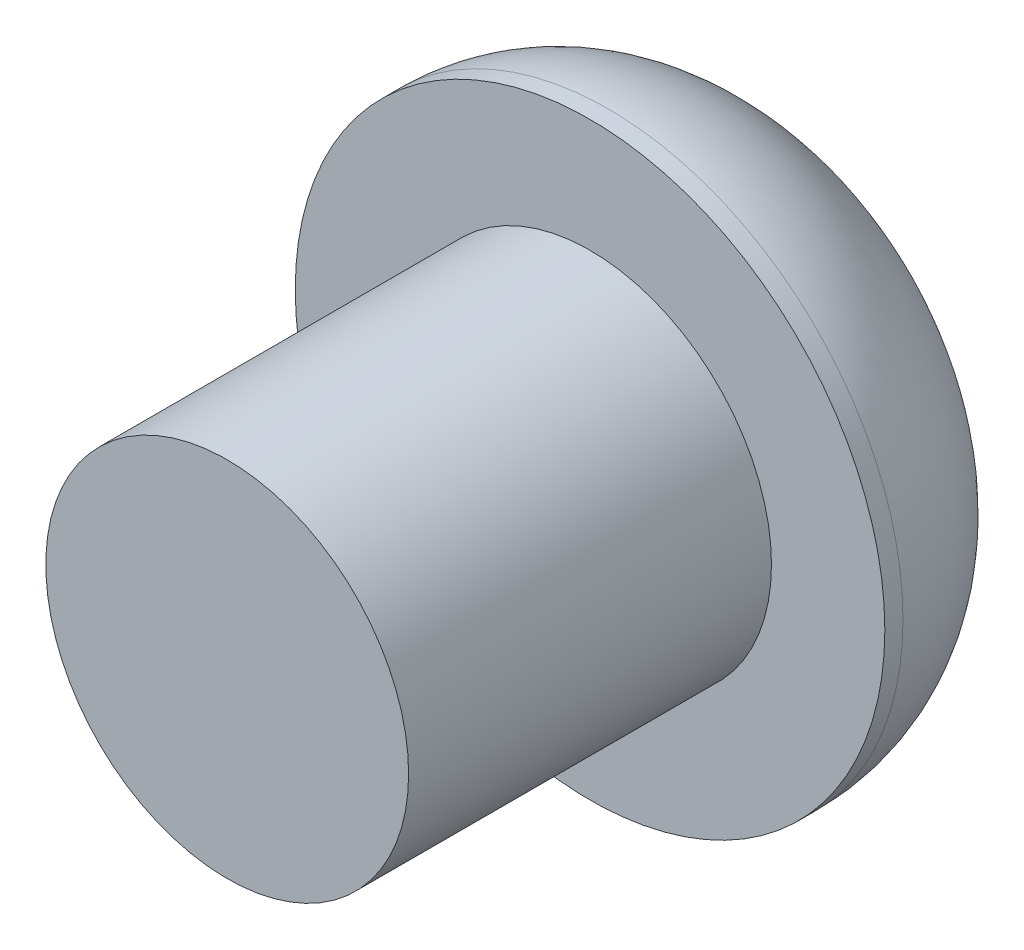
SolidWorks part; units mm, degrees
ref_plane "前视基准面" through (0, 0, 0) normal (0, 0, 1) x (1, 0, 0)
ref_plane "上视基准面" through (0, 0, 0) normal (0, 1, 0) x (1, 0, 0)
ref_plane "右视基准面" through (0, 0, 0) normal (1, 0, 0) x (0, 0, -1)
sketch "草图1" plane through (0, 0, 0) normal (0, 0, 1) x (1, 0, 0)
  circle A0 centre (0, 0) radius 2
  dimension "D1" = 4
extrude "凸台-拉伸1" add sketch "草图1" along normal blind 4
sketch "草图2" plane through (0, 0, 0) normal (0, 0, -1) x (-1, 0, 0)
  circle A0 centre (0, 0) radius 3.25
  dimension "D1" = 6.5
extrude "凸台-拉伸2" add sketch "草图2" along normal blind 2.2
fillet "圆角1" radius 2 1 edges at (-3.25, 0, -2.2)
sketch "草图3" plane through (0, 0, -2.2) normal (0, 0, -1) x (-1, 0, 0)
  line L0 (0, 3.24) -> (0, -3.24) construction
  line L1 (-3.24, 0) -> (3.24, 0) construction
  line L2 (-3.24, 0.25) -> (3.24, 0.25) construction
  line L3 (0.25, 3.24) -> (0.25, -3.24) construction
  line L4 (-3.24, -0.25) -> (3.24, -0.25) construction
  line L5 (-0.25, 3.24) -> (-0.25, -3.24) construction
  line L7 (3.24, 0.25) -> (3.24, -0.25)
  line L8 (-0.25, 3.24) -> (0.25, 3.24)
  line L10 (-0.25, 3.24) -> (-0.25, 0.25)
  line L11 (0.25, 3.24) -> (0.25, 0.25)
  line L12 (3.24, 0.25) -> (0.25, 0.25)
  line L13 (3.24, -0.25) -> (0.25, -0.25)
  line L15 (0.25, -3.24) -> (0.25, -0.25)
  line L16 (-0.25, -3.24) -> (-0.25, -0.25)
  line L17 (0.25, -3.24) -> (-0.25, -3.24)
  line L18 (-3.24, -0.25) -> (-0.25, -0.25)
  line L19 (-3.24, 0.25) -> (-0.25, 0.25)
  line L20 (-3.24, -0.25) -> (-3.24, 0.25)
  line L21 (3.24, 0.25) -> (3.24, -0.25) [skipped]
  circle A1 centre (0, 0) radius 3.24 construction
  dimension "D1" = 0.25
  dimension "D2" = 0.25
  dimension "D3" = 4
extrude "切除-拉伸1" cut sketch "草图3" against normal blind 0.5
